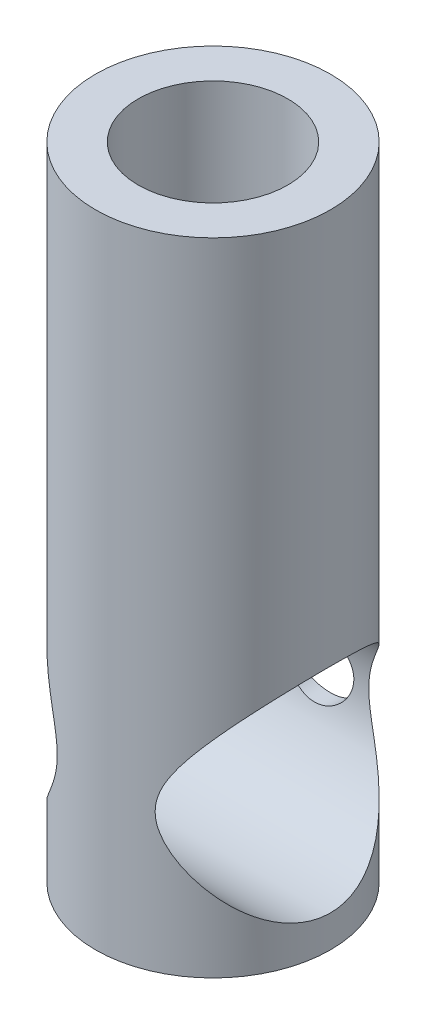
SolidWorks part; units mm, degrees
ref_plane "Front Plane" through (0, 0, 0) normal (0, 0, 1) x (1, 0, 0)
ref_plane "Top Plane" through (0, 0, 0) normal (0, 1, 0) x (1, 0, 0)
ref_plane "Right Plane" through (0, 0, 0) normal (1, 0, 0) x (0, 0, -1)
sketch "Sketch1" plane through (0, 0, 0) normal (0, 1, 0) x (1, 0, 0)
  circle A0 centre (0, 0) radius 55
  dimension "D1" = 110
sketch "Sketch5" plane through (0, 0, 0) normal (1, 0, 0) x (0, 0, -1)
  circle A0 centre (0, 65) radius 50
  dimension "D1" = 100
extrude "Boss-Extrude1" add sketch "Sketch1" along normal blind 300
extrude "Cut-Extrude2" cut sketch "Sketch5" against normal through all both and the other way through all contours A0
sketch "Sketch8" plane through (0, 300, 0) normal (0, 1, 0) x (1, 0, 0)
  circle A0 centre (0, 0) radius 55
  dimension "D1" = 110
sketch "Sketch9" plane through (0, 300, 0) normal (0, 1, 0) x (1, 0, 0)
  circle A0 centre (0, 0) radius 35
extrude "Cut-Extrude3" cut sketch "Sketch9" against normal blind 211
sketch "Sketch10" plane through (0, 0, 0) normal (0, 0, 1) x (1, 0, 0)
  circle A0 centre (0, 65.185) radius 15.9159
extrude "Cut-Extrude4" cut sketch "Sketch10" against normal blind 177
